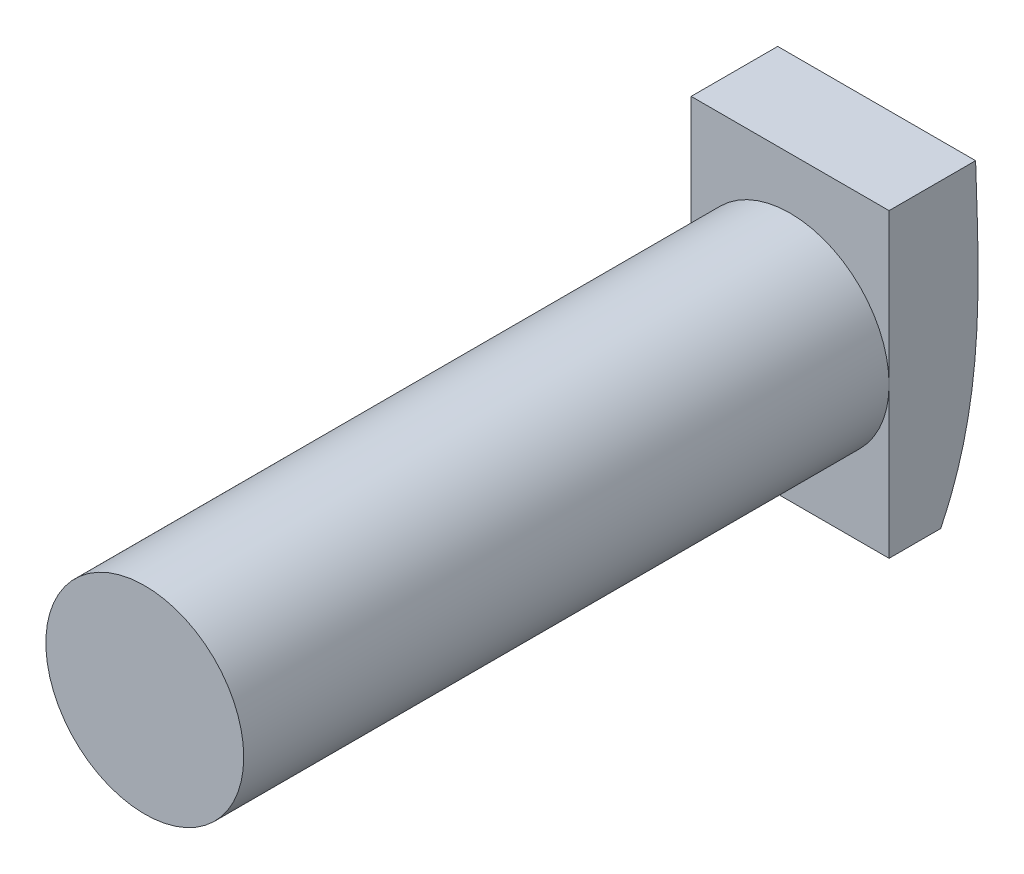
SolidWorks part; units mm, degrees
ref_plane "Front Plane" through (0, 0, 0) normal (0, 0, 1) x (1, 0, 0)
ref_plane "Top Plane" through (0, 0, 0) normal (0, 1, 0) x (1, 0, 0)
ref_plane "Right Plane" through (0, 0, 0) normal (1, 0, 0) x (0, 0, -1)
sketch "Sketch1" plane through (0, 0, 0) normal (0, 0, 1) x (1, 0, 0)
  circle A0 centre (0, 0) radius 2.3
  dimension "D1" = 4.6
extrude "Boss-Extrude1" add sketch "Sketch1" along normal blind 15
sketch "Sketch2" plane through (0, 0, 0) normal (0, 0, -1) x (-1, 0, 0)
  line L1 (-2.3, -3.5) -> (2.3, -3.5)
  line L2 (-2.3, -3.5) -> (-2.3, 3.5)
  line L3 (-2.3, 3.5) -> (2.3, 3.5)
  line L4 (2.3, -3.5) -> (2.3, 3.5)
  line L5 (-2.3, -3.5) -> (2.3, 3.5) construction
  line L6 (-2.3, 3.5) -> (2.3, -3.5) construction
  circle A0 centre (0, 0) radius 2.3 construction
  point P0 (0, 0)
  dimension "D1" = 7
extrude "Boss-Extrude2" add sketch "Sketch2" along normal blind 3
sketch "Sketch3" plane through (2.3, 0, 0) normal (1, 0, 0) x (0, 0, -1)
  line L0 (3, 3.5) -> (0, 3.5) construction
  line L1 (3, -3.5) -> (0, -3.5) construction
  line L2 (0, 0) -> (0, -3.5) construction
  line L3 (0, 3.5) -> (0, 0) construction
  line L4 (1.2, -3.5) -> (3, -3.5)
  line L5 (3, -3.5) -> (3, 3.5)
  line L6 (3, 3.5) -> (2.0115, 3.5)
  line L7 (3, 3.5) -> (0, 3.5) construction
  spline S0 degree 3 poles (1.2, -3.5) (2.2675, -1.3344) (2.0824, 1.1824) (2.0115, 3.5) knots 0 0 0 0 1 1 1 1
  dimension "D1" = 1.2
  dimension "D2" = 2
extrude "Cut-Extrude1" cut sketch "Sketch3" against normal up to vertex (4.6 mm away)
